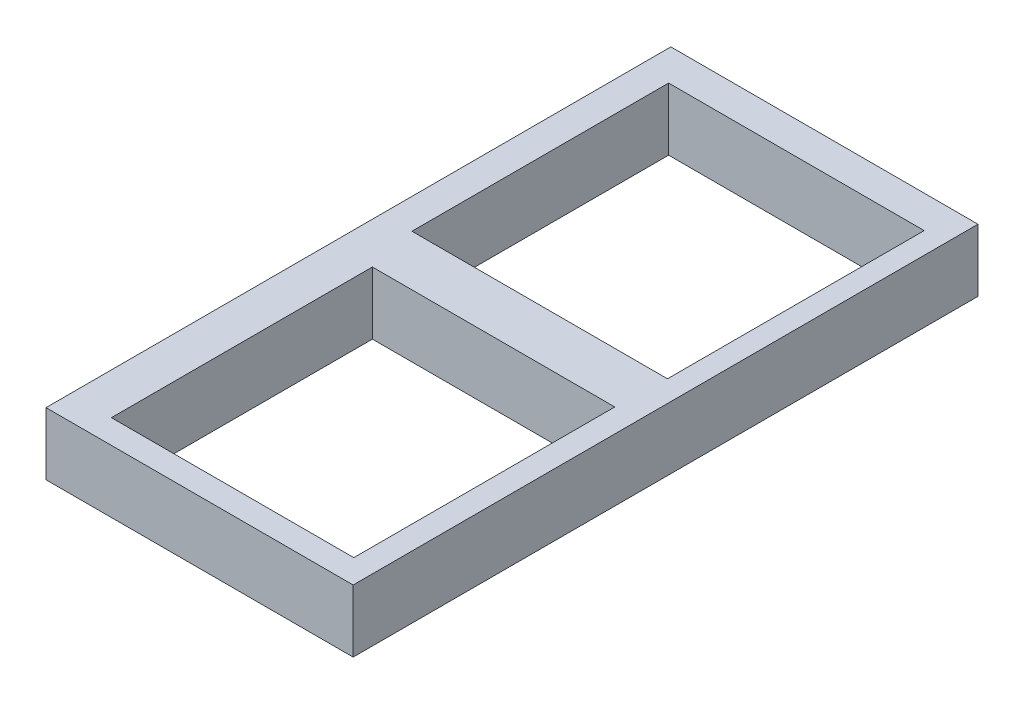
SolidWorks part; units mm, degrees
ref_plane "Front Plane" through (0, 0, 0) normal (0, 0, 1) x (1, 0, 0)
ref_plane "Top Plane" through (0, 0, 0) normal (0, 1, 0) x (1, 0, 0)
ref_plane "Right Plane" through (0, 0, 0) normal (1, 0, 0) x (0, 0, -1)
sketch "Sketch1" plane through (0, 0, 0) normal (0, 1, 0) x (1, 0, 0)
  line L1 (-24.5775, 50) -> (24.5775, 50)
  line L2 (-24.5775, 50) -> (-24.5775, -50)
  line L3 (-24.5775, -50) -> (24.5775, -50)
  line L4 (24.5775, 50) -> (24.5775, -50)
  line L5 (-24.5775, 50) -> (24.5775, -50) construction
  line L6 (-24.5775, -50) -> (24.5775, 50) construction
  point P0 (0, 0)
  dimension "D1" = 100
extrude "Boss-Extrude1" add sketch "Sketch1" along normal blind 10
sketch "Sketch2" plane through (0, 0, 0) normal (0, -1, 0) x (-1, 0, 0)
  line L1 (-21.1553, 44.8094) -> (19.7443, 44.8094)
  line L2 (-21.1553, 44.8094) -> (-21.1553, 3.7295)
  line L3 (-21.1553, 3.7295) -> (19.7443, 3.7295)
  line L4 (19.7443, 44.8094) -> (19.7443, 3.7295)
  line L5 (-21.1553, 44.8094) -> (19.7443, 3.7295) construction
  line L6 (-21.1553, 3.7295) -> (19.7443, 44.8094) construction
  line L7 (-20.8404, -4.3909) -> (17.9533, -4.3909)
  line L8 (-20.8404, -4.3909) -> (-20.8404, -46.157)
  line L9 (-20.8404, -46.157) -> (17.9533, -46.157)
  line L10 (17.9533, -4.3909) -> (17.9533, -46.157)
  line L11 (-20.8404, -4.3909) -> (17.9533, -46.157) construction
  line L12 (-20.8404, -46.157) -> (17.9533, -4.3909) construction
  point P0 (-0.7055, 24.2695)
  point P5 (-1.4436, -25.2739)
extrude "Cut-Extrude1" cut sketch "Sketch2" against normal through all
